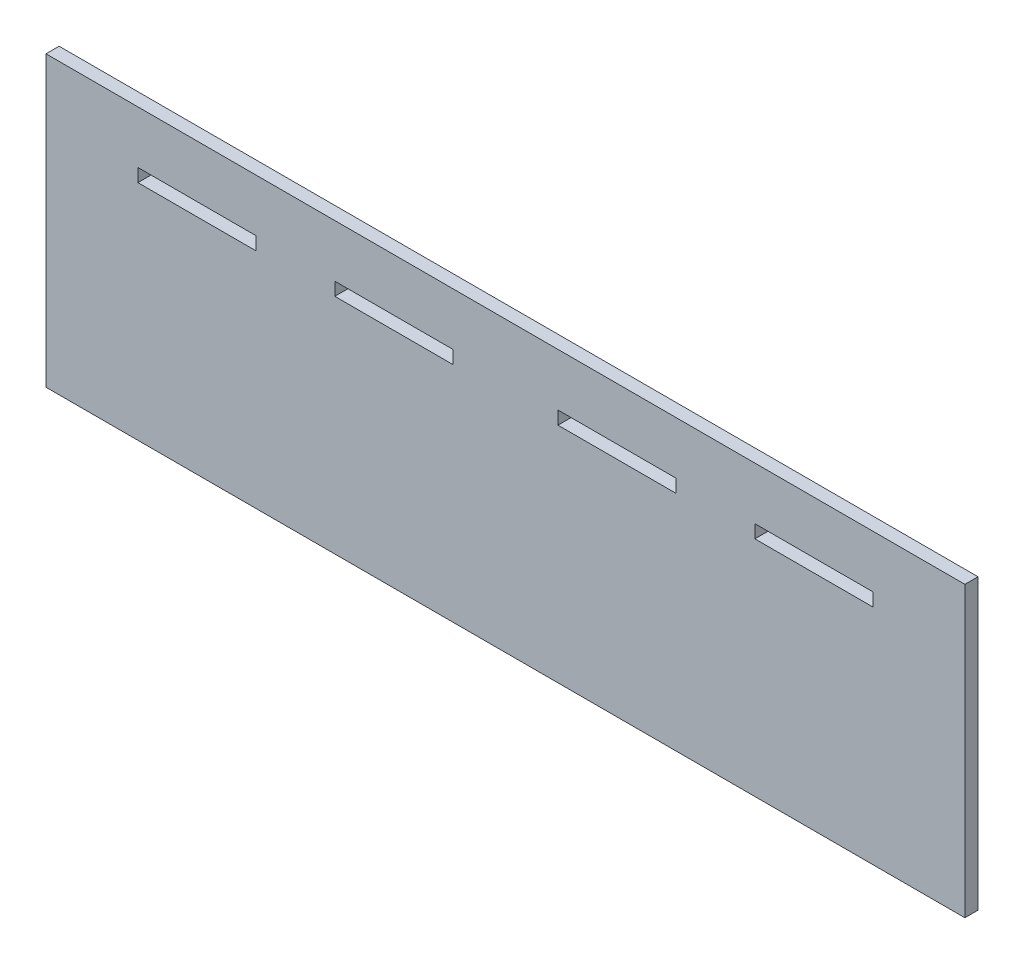
SolidWorks part; units mm, degrees
ref_plane "Plan de face" through (0, 0, 0) normal (0, 0, 1) x (1, 0, 0)
ref_plane "Plan de dessus" through (0, 0, 0) normal (0, 1, 0) x (1, 0, 0)
ref_plane "Plan de droite" through (0, 0, 0) normal (1, 0, 0) x (0, 0, -1)
sketch "Esquisse1" plane through (0, 0, 0) normal (0, 0, 1) x (1, 0, 0)
  line L0 (0, 220) -> (700, 220)
  line L1 (0, 0) -> (700, 0)
  line L2 (0, 0) -> (0, 220)
  line L3 (0, 180) -> (700, 180) construction
  line L4 (700, 0) -> (700, 220)
  line L5 (700, 175) -> (0, 175) construction
  line L6 (0, 170) -> (700, 170) construction
  line L7 (390, 170) -> (310, 170) construction
  line L8 (220, 180) -> (310, 180)
  line L9 (220, 180) -> (220, 170)
  line L10 (220, 170) -> (310, 170)
  line L11 (310, 180) -> (310, 170)
  line L12 (390, 180) -> (480, 180)
  line L13 (390, 180) -> (390, 170)
  line L14 (390, 170) -> (480, 170)
  line L15 (480, 180) -> (480, 170)
  line L16 (350, 170) -> (350, 180) construction
  line L18 (540, 180) -> (630, 180)
  line L19 (540, 180) -> (540, 170)
  line L20 (540, 170) -> (630, 170)
  line L21 (630, 180) -> (630, 170)
  line L22 (70, 180) -> (160, 180)
  line L23 (70, 180) -> (70, 170)
  line L24 (70, 170) -> (160, 170)
  line L25 (160, 180) -> (160, 170)
  dimension "D1" = 10
  dimension "D2" = 5
  dimension "D3" = 40
  dimension "D4" = 220
  dimension "D5" = 700
  dimension "D6" = 90
  dimension "D7" = 80
  dimension "D8" = 90
  dimension "D9" = 90
  dimension "D10" = 60
  dimension "D11" = 90
  dimension "D12" = 60
extrude "Boss.-Extru.1" add sketch "Esquisse1" along normal blind 10
